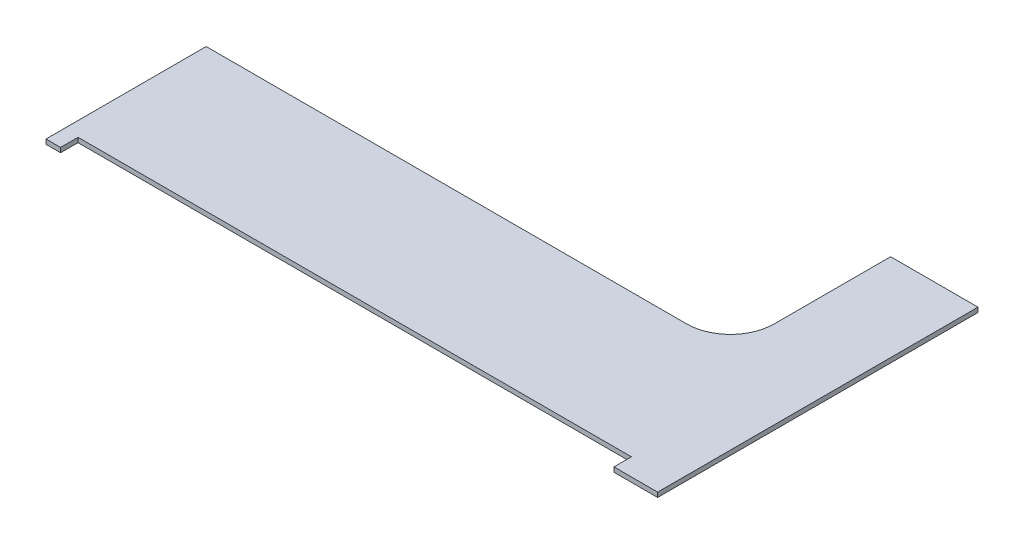
SolidWorks part; units mm, degrees
ref_plane "Ebene vorne" through (0, 0, 0) normal (0, 0, 1) x (1, 0, 0)
ref_plane "Ebene oben" through (0, 0, 0) normal (0, 1, 0) x (1, 0, 0)
ref_plane "Ebene rechts" through (0, 0, 0) normal (1, 0, 0) x (0, 0, -1)
sketch "Skizze1" plane through (0, 0, 0) normal (0, 1, 0) x (1, 0, 0)
  line L0 (2100, 0) -> (2100, 1100)
  line L1 (0, 0) -> (2100, 0)
  line L2 (0, 0) -> (0, 550)
  line L3 (0, 550) -> (1650, 550)
  line L7 (2100, 1100) -> (1800, 1100)
  line L8 (1800, 1100) -> (1800, 700)
  arc A0 (1800, 700) -> (1650, 550) centre (1650, 700) cw
  point P0 (0, 0)
  point P1 (0, 0)
  point P11 (344.3988, 341.9432)
  point P12 (1000.0661, -266.2698)
  point P13 (0, 0)
  dimension "D4" = 1100
  dimension "150" = 150
  dimension "D1" = 550
  dimension "D2" = 2100
  dimension "D3" = 300
extrude "Aufsatz-Linear austragen1" add sketch "Skizze1" along normal blind 16
sketch "Skizze2" plane through (0, 16, 0) normal (0, 1, 0) x (1, 0, 0)
  line L0 (0, 0) -> (2100, 0) construction
  line L1 (50, 0) -> (1950, 0)
  line L2 (50, 0) -> (50, 60)
  line L3 (50, 60) -> (1950, 60)
  line L4 (1950, 0) -> (1950, 60)
  line L5 (2100, 0) -> (2100, 1100) construction
  line L6 (0, 550) -> (0, 0) construction
  dimension "D1" = 60
  dimension "D2" = 150
  dimension "D3" = 50
extrude "Schnitt-Linear austragen1" cut sketch "Skizze2" against normal through all
